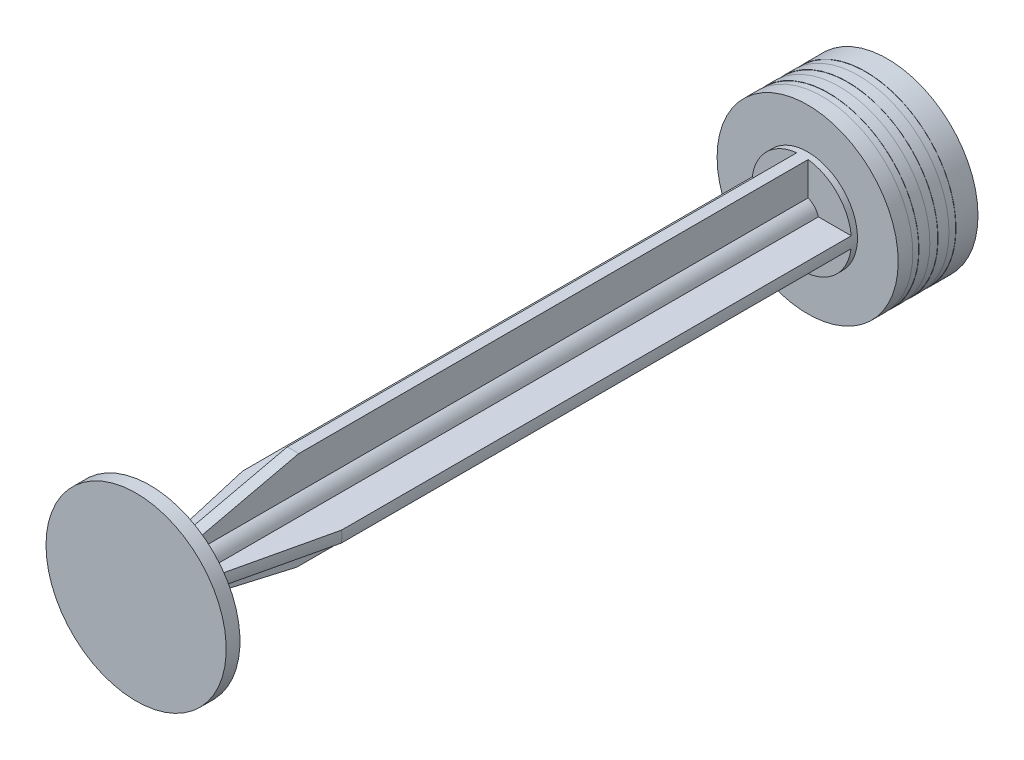
SolidWorks part; units mm, degrees
ref_plane "Top plane" through (0, 0, 0) normal (0, 0, 1) x (1, 0, 0)
ref_plane "Right plane" through (0, 0, 0) normal (0, 1, 0) x (1, 0, 0)
ref_plane "Front plane" through (0, 0, 0) normal (1, 0, 0) x (0, 0, -1)
sketch "Sketch2" plane through (0, 0, -44.3022) normal (0, 0, 1) x (1, 0, 0)
  circle A0 centre (-124.1564, -50.7982) radius 6.8064
extrude "Boss-Extrude1" add sketch "Sketch2" against normal blind 6
ref_plane "Plane1" through (-124.1564, 0, 0) normal (-1, 0, 0) x (0, 0, 1)
sketch "Sketch3" plane through (-124.1564, 0, 0) normal (-1, 0, 0) x (0, 0, 1)
  line L0 (-44.3022, -50.7982) -> (6.1832, -50.7982)
  line L1 (-44.3022, -57.6045) -> (-44.3022, -43.9918) construction
  line L2 (6.1832, -44.0243) -> (6.1832, -50.7982)
  line L3 (5.1488, -44.0243) -> (6.1832, -44.0243)
  line L4 (5.1488, -49.4877) -> (5.1488, -44.0243)
  line L5 (5.1488, -49.4877) -> (-5.5389, -47.0527)
  line L6 (-44.3022, -47.0527) -> (-5.5389, -47.0527)
  line L7 (-44.3022, -47.0527) -> (-44.3022, -50.7982)
revolve "Revolve1" add sketch "Sketch3" angle 360 about L0
sketch "Sketch4" plane through (0, 0, 5.1488) normal (0, 0, -1) x (-1, 0, 0)
  line L0 (123.6697, -49.9246) -> (123.6697, -46.252)
  line L1 (123.6697, -46.252) -> (124.5241, -46.252)
  line L2 (124.5241, -46.252) -> (124.5241, -49.8682)
  line L3 (128.7025, -51.1659) -> (125.0863, -51.1659)
  line L4 (128.7025, -50.3115) -> (128.7025, -51.1659)
  line L5 (125.0299, -50.3115) -> (128.7025, -50.3115)
  line L6 (123.7886, -55.3443) -> (123.7886, -51.7281)
  line L7 (124.6431, -55.3443) -> (123.7886, -55.3443)
  line L8 (124.6431, -51.6717) -> (124.6431, -55.3443)
  line L9 (119.6102, -50.4304) -> (123.2265, -50.4304)
  line L10 (119.6102, -51.2849) -> (119.6102, -50.4304)
  line L11 (123.2828, -51.2849) -> (119.6102, -51.2849)
  circle A0 centre (124.1564, -50.7982) radius 1
  circle A1 centre (124.1564, -50.7982) radius 1
  circle A2 centre (124.1564, -50.7982) radius 1
  circle A3 centre (124.1564, -50.7982) radius 1
  circle A4 centre (124.1564, -50.7982) radius 4.5462
  point P24 (124.1564, -50.7982)
  circle M3 centre (124.1564, -50.7982) radius 1.3105
  dimension "D1" = 4
extrude "Cut-Extrude1" cut sketch "Sketch4" along normal blind 49 contours L0 A4 L9 M3 | L5 A4 L2 M3 | L8 A4 L3 M3 | L11 A4 L6 M3
sketch "Sketch5" plane through (-124.1564, 0, 0) normal (-1, 0, 0) x (0, 0, 1)
  line L0 (-50.3022, -50.7982) -> (-49.4047, -43.9918)
  line L1 (-50.3022, -43.9918) -> (-50.3022, -57.6045) construction
  line L2 (-44.3022, -43.9918) -> (-50.3022, -43.9918) construction
  line L3 (-49.4047, -43.9918) -> (-48.6526, -43.9918)
  line L4 (-48.6526, -43.9918) -> (-48.6526, -44.011)
  line L5 (-48.6526, -44.011) -> (-48.1262, -44.011)
  line L6 (-48.1262, -44.011) -> (-48.1262, -43.9918)
  line L7 (-48.1262, -43.9918) -> (-47.3022, -43.9918)
  line L8 (-47.3022, -43.9918) -> (-47.3022, -44.011)
  line L9 (-47.3022, -44.011) -> (-46.6834, -44.011)
  line L10 (-46.6834, -44.011) -> (-46.6834, -43.9918)
  line L11 (-46.6834, -43.9918) -> (-45.8699, -43.9918)
  line L12 (-45.8699, -44.011) -> (-45.8699, -43.9918)
  line L13 (-45.8699, -44.011) -> (-45.4005, -44.011)
  line L14 (-45.4005, -44.011) -> (-45.4005, -43.9918)
  line L15 (-50.3022, -43.9918) -> (-50.3022, -50.7982)
  line L16 (-50.3022, -43.9918) -> (-49.4047, -43.9918)
  line L17 (-45.4005, -43.9918) -> (-48.6526, -43.9918)
revolve "Cut-Revolve2" cut sketch "Sketch5" angle 360 about axis through (-124.1564, -50.7982, -50.3022) along (0, 0, 1)
sketch "Sketch6" plane through (-124.1564, 0, 0) normal (-1, 0, 0) x (0, 0, 1)
  line L1 (-50.3022, -43.9918) -> (-50.3022, -57.6045) construction
  line L5 (-50.3022, -50.7982) -> (-39.4089, -50.7982) construction
  line L6 (-43.8512, -50.7982) -> (5.1488, -50.7982) construction
  line L7 (-50.3022, -50.7982) -> (-48.9409, -41.8846)
  line L9 (-48.9409, -41.8846) -> (-52.6354, -41.8846)
  line L10 (-52.6354, -41.8846) -> (-50.3022, -50.7982)
sketch "Sketch7" plane through (0, -50.4304, 0) normal (0, 1, 0) x (1, 0, 0)
  line L0 (-123.6697, -5.1488) -> (-123.6697, 5.5389) construction
  circle A0 centre (-123.6697, -2.4753) radius 0.8545
extrude "Cut-Extrude2" cut sketch "Sketch7" against normal blind 10
